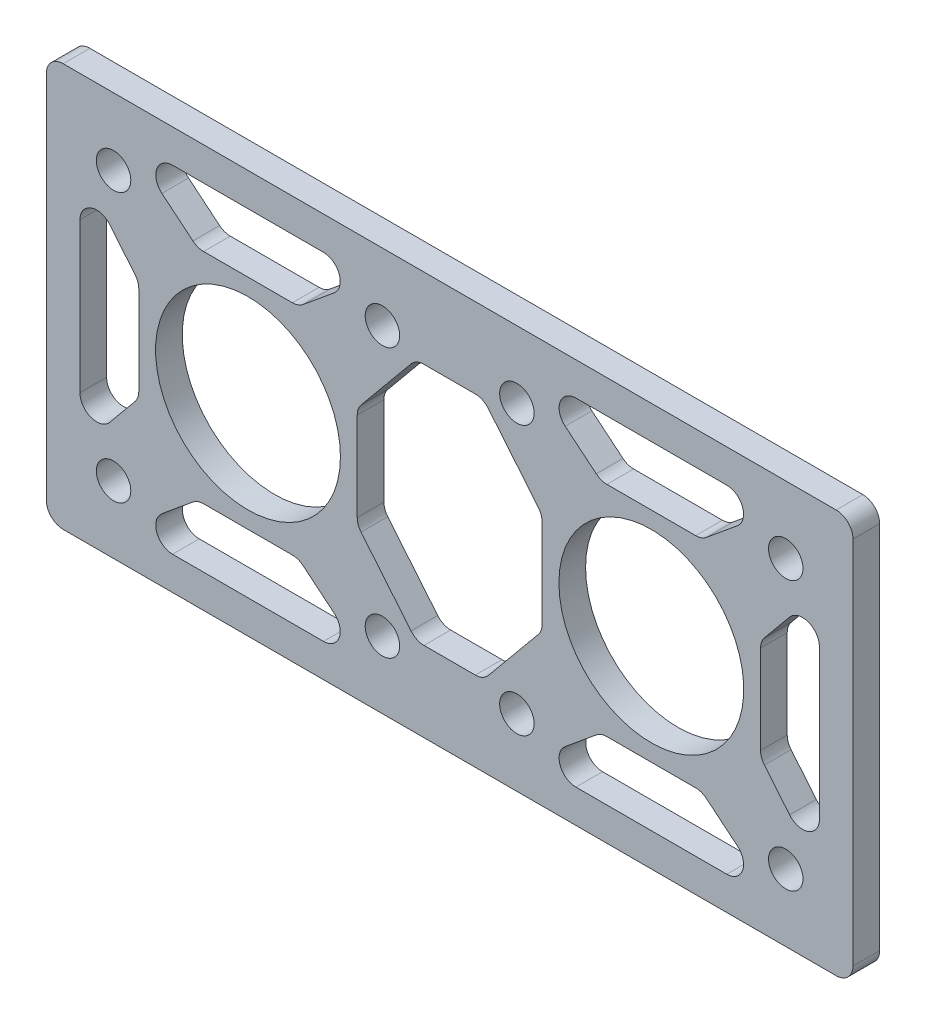
SolidWorks part; units mm, degrees
ref_plane "Front Plane" through (0, 0, 0) normal (0, 0, 1) x (1, 0, 0)
ref_plane "Top Plane" through (0, 0, 0) normal (0, 1, 0) x (1, 0, 0)
ref_plane "Right Plane" through (0, 0, 0) normal (1, 0, 0) x (0, 0, -1)
sketch "Sketch1" plane through (0, 0, 0) normal (0, 0, 1) x (1, 0, 0)
  line L0 (0, 0) -> (50000, 0) construction
  line L1 (48, -24) -> (-48, -24)
  line L2 (48, -24) -> (48, 24)
  line L3 (48, 24) -> (-48, 24)
  line L4 (-48, -24) -> (-48, 24)
  line L5 (48, -24) -> (-48, 24) construction
  line L6 (48, 24) -> (-48, -24) construction
  line L7 (0, 0) -> (0, -50000) construction
  line L8 (-38.5449, 20.05) -> (-30, 13)
  line L9 (-40, 16) -> (-8, 16) construction
  line L10 (-40, 16) -> (-40, -16) construction
  line L11 (-40, -16) -> (-8, -16) construction
  line L12 (-8, 16) -> (-8, -16) construction
  line L13 (-40, 16) -> (-8, -16) construction
  line L14 (-40, -16) -> (-8, 16) construction
  line L15 (-30, 13) -> (-18, 13)
  line L16 (-18, 13) -> (-9.4551, 20.05)
  line L17 (-9.4551, 20.05) -> (-38.5449, 20.05)
  line L18 (50, 26) -> (-50, 26) construction
  line L19 (-50, -26) -> (-50, 26) construction
  line L20 (50, -26) -> (-50, -26) construction
  line L21 (50, -26) -> (50, 26) construction
  line L22 (44, 20) -> (-44, 20) construction
  line L23 (-44, -20) -> (-44, 20) construction
  line L24 (44, -20) -> (-44, -20) construction
  line L25 (44, -20) -> (44, 20) construction
  line L26 (-18, -13) -> (-9.4551, -20.05)
  line L27 (-30, -13) -> (-18, -13)
  line L28 (-38.5449, -20.05) -> (-30, -13)
  line L29 (-9.4551, -20.05) -> (-38.5449, -20.05)
  line L30 (-44, 14.4843) -> (-44, -14.4843) construction
  line L31 (-44, -14.4843) -> (-37, -6) construction
  line L32 (-37, -6) -> (-37, 6) construction
  line L33 (-37, 6) -> (-44, 14.4843) construction
  line L34 (-24, 0) -> (-24, 50000) construction
  line L35 (-11, -6) -> (-11, 6)
  line L36 (-4, -14.4843) -> (-11, -6)
  line L38 (-11, 6) -> (-4, 14.4843)
  line L39 (4, -14.4843) -> (11, -6)
  line L41 (11, 6) -> (4, 14.4843)
  line L42 (11, -6) -> (11, 6)
  line L43 (30, -13) -> (18, -13)
  line L44 (38.5449, -20.05) -> (30, -13)
  line L45 (9.4551, -20.05) -> (38.5449, -20.05)
  line L46 (18, -13) -> (9.4551, -20.05)
  line L47 (37, -6) -> (37, 6)
  line L48 (44, -14.4843) -> (37, -6)
  line L49 (44, 14.4843) -> (44, -14.4843)
  line L50 (37, 6) -> (44, 14.4843)
  line L51 (18, 13) -> (9.4551, 20.05)
  line L52 (30, 13) -> (18, 13)
  line L53 (38.5449, 20.05) -> (30, 13)
  line L54 (9.4551, 20.05) -> (38.5449, 20.05)
  line L55 (-44, -14.4843) -> (-37, -6)
  line L56 (-44, 14.4843) -> (-44, -14.4843)
  line L57 (-37, 6) -> (-44, 14.4843)
  line L58 (-37, -6) -> (-37, 6)
  line L59 (-4, 14.4843) -> (4, 14.4843)
  line L60 (-4, -14.4843) -> (4, -14.4843)
  circle A0 centre (-40, 16) radius 2.05
  circle A1 centre (-8, 16) radius 2.05
  circle A2 centre (-8, -16) radius 2.05
  circle A3 centre (-40, -16) radius 2.05
  circle A4 centre (-24, 0) radius 11
  circle A5 centre (-8, -16) radius 4.05 construction
  circle A6 centre (-40, -16) radius 4.05 construction
  circle A7 centre (-24, 0) radius 13 construction
  circle A8 centre (-40, 16) radius 4.05 construction
  circle A9 centre (-8, 16) radius 4.05 construction
  circle A10 centre (-8, -16) radius 0.05 construction
  circle A11 centre (-40, -16) radius 0.05 construction
  circle A12 centre (-24, 0) radius 9 construction
  circle A13 centre (-40, 16) radius 0.05 construction
  circle A14 centre (-8, 16) radius 0.05 construction
  circle A15 centre (8, 16) radius 2.05
  circle A16 centre (8, -16) radius 2.05
  circle A17 centre (40, -16) radius 2.05
  circle A18 centre (24, 0) radius 11
  circle A19 centre (40, 16) radius 2.05
  circle A20 centre (-36.7, 0) radius 2.05 construction
  circle A21 centre (11.3, 0) radius 2.05 construction
  point P0 (0, 0)
  point P10 (-24, 0)
  dimension "D5" = 4.1
  dimension "D6" = 22
  dimension "D1" = 96
  dimension "D2" = 48
  dimension "D3" = 32
  dimension "D4" = 8
  dimension "D11" = 12
  dimension "D12" = 12
  dimension "D13" = 48
  dimension "D14" = 11.3
  dimension "D7" = 2
  dimension "D8" = 2
  dimension "D9" = 2
  dimension "D10" = 4
extrude "Boss-Extrude1" add sketch "Sketch1" along normal blind 3.175
fillet "Fillet1" radius 2 36 edges at (38.5449, -20.05, 1.5875) (9.4551, -20.05, 1.5875) (18, -13, 1.5875) (30, -13, 1.5875) (44, -14.4843, 1.5875) (37, -6, 1.5875) (37, 6, 1.5875) (44, 14.4843, 1.5875) (30, 13, 1.5875) (38.5449, 20.05, 1.5875) (9.4551, 20.05, 1.5875) (18, 13, 1.5875) (-48, -24, 1.5875) (-38.5449, -20.05, 1.5875) (-9.4551, -20.05, 1.5875) (-11, -6, 1.5875) (-30, -13, 1.5875) (-18, -13, 1.5875) (-11, 6, 1.5875) (-9.4551, 20.05, 1.5875) (-38.5449, 20.05, 1.5875) (-30, 13, 1.5875) (-18, 13, 1.5875) (-48, 24, 1.5875) (48, 24, 1.5875) (48, -24, 1.5875) (11, -6, 1.5875) (11, 6, 1.5875) (-44, -14.4843, 1.5875) (-37, -6, 1.5875) (-44, 14.4843, 1.5875) (-37, 6, 1.5875) (-4, -14.4843, 1.5875) (4, -14.4843, 1.5875) (4, 14.4843, 1.5875) (-4, 14.4843, 1.5875)
